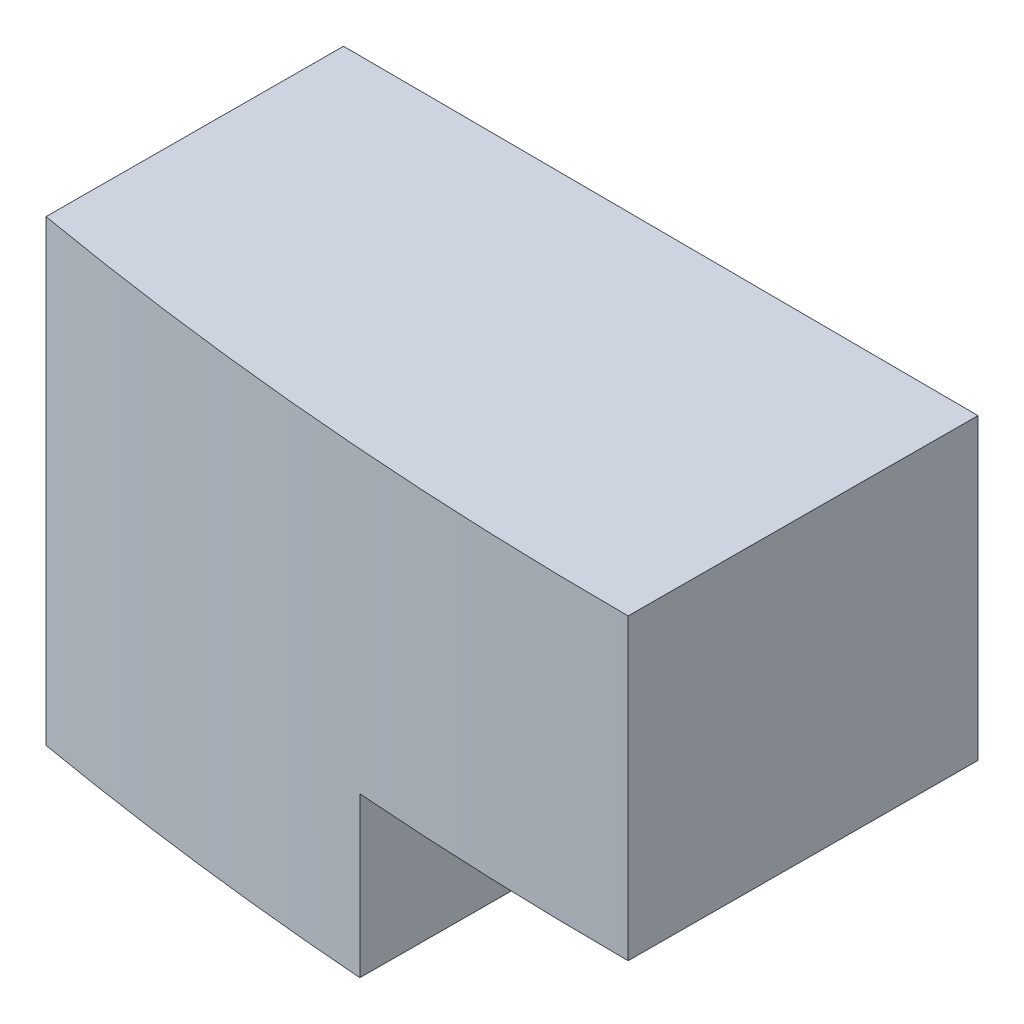
SolidWorks part; units mm, degrees
ref_plane "Plano frontal" through (0, 0, 0) normal (0, 0, 1) x (1, 0, 0)
ref_plane "Plano superior" through (0, 0, 0) normal (0, 1, 0) x (1, 0, 0)
ref_plane "Plano direito" through (0, 0, 0) normal (1, 0, 0) x (0, 0, -1)
sketch "Esboço1" plane through (0, 0, 0) normal (0, 1, 0) x (1, 0, 0)
  line L0 (0, 0) -> (0, -75) construction
  line L10 (0, -75) -> (0.0293, -68)
  line L11 (0.0293, -68) -> (-12.7706, -67.9464)
  line L12 (-12.7706, -67.9464) -> (-12.7955, -73.9004)
  arc A2 (-12.7955, -73.9004) -> (0, -75) centre (0, 0) ccw
  dimension "D1" = 75
  dimension "D4" = 12.8
  dimension "D2" = 7
  dimension "D3" = 0.24
extrude "Ressalto-extrusão1" add sketch "Esboço1" along normal blind 9.2
sketch "Esboço3" plane through (-0.2848, 0, 67.9987) normal (0.0042, 0, -1) x (-1, 0, -0.0042)
  line L0 (-0.3142, 9.2) -> (-0.3142, 0) construction
  line L1 (-0.3142, 3.2) -> (5.2858, 3.2)
  line L2 (-0.3142, 3.2) -> (-0.3142, 0)
  line L3 (-0.3142, 0) -> (5.2858, 0)
  line L4 (5.2858, 3.2) -> (5.2858, 0)
  line L5 (-0.3142, 0) -> (12.4858, 0) construction
  line L6 (-0.3142, 9.2) -> (12.4858, 9.2) construction
  dimension "D1" = 6
  dimension "D2" = 5.6
extrude "Corte-extrusão1" cut sketch "Esboço3" against normal through all
